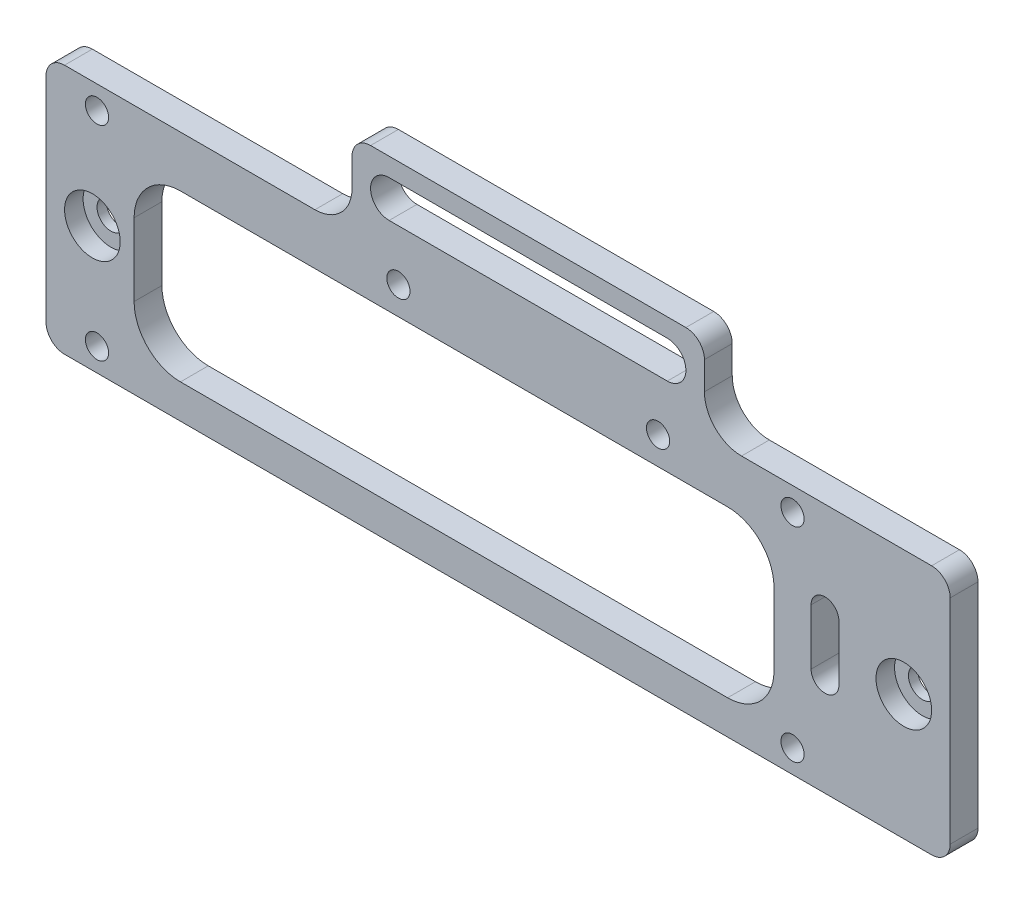
SolidWorks part; units mm, degrees
material "3.0205 (EN-AW 1200)"
ref_plane "前视基准面" through (0, 0, 0) normal (0, 0, 1) x (1, 0, 0)
ref_plane "上视基准面" through (0, 0, 0) normal (0, 1, 0) x (1, 0, 0)
ref_plane "右视基准面" through (0, 0, 0) normal (1, 0, 0) x (0, 0, -1)
other "Configuration Table"
sketch "草图3" plane through (0, 0, 0) normal (0, 0, 1) x (1, 0, 0)
  line L2 (-48.75, 13.5) -> (-48.75, -13.5)
  line L3 (-48.75, -13.5) -> (48.75, -13.5)
  line L4 (48.75, 13.5) -> (48.75, -13.5)
  line L5 (-48.75, 13.5) -> (48.75, -13.5) construction
  line L6 (-48.75, -13.5) -> (48.75, 13.5) construction
  line L16 (-48.75, 13.5) -> (48.75, 13.5)
  point P0 (0, 0)
  dimension "D1" = 97.5
  dimension "D2" = 27
extrude "凸台-拉伸1" add sketch "草图3" along normal blind 3
sketch "草图4" plane through (0, 0, 3) normal (0, 0, 1) x (1, 0, 0)
  line L0 (-48.75, 13.5) -> (-48.75, -13.5) construction
  line L2 (48.75, 13.5) -> (-48.75, 13.5) construction
  circle A0 centre (-43.25, 11) radius 1.25
  circle A1 centre (-43.25, -11) radius 1.25
  circle A2 centre (31.75, 11) radius 1.25
  circle A3 centre (31.75, -11) radius 1.25
  circle A4 centre (17.25, 11) radius 1.25
  circle A5 centre (-10.75, 11) radius 1.25
  dimension "D1" = 2.5
  dimension "D2" = 2.5
  dimension "D3" = 2.5
  dimension "D4" = 2.5
  dimension "D9" = 2.5
  dimension "D10" = 2.5
  dimension "D5" = 5.5
  dimension "D6" = 2.5
  dimension "D7" = 22
  dimension "D8" = 75
  dimension "D11" = 14.5
  dimension "D12" = 28
extrude "切除-拉伸1" cut sketch "草图4" against normal through all
sketch "草图7" plane through (0, 0, 0) normal (0, 0, -1) x (-1, 0, 0)
  line L0 (48.75, 13.5) -> (48.75, -13.5) construction
  line L1 (48.75, -3.5) -> (44.75, -3.5)
  line L2 (48.75, -3.5) -> (48.75, 4.5)
  line L3 (48.75, 4.5) -> (44.75, 4.5)
  line L4 (44.75, -3.5) -> (44.75, 4.5)
  line L5 (-48.75, -13.5) -> (-48.75, 13.5) construction
  line L6 (-48.75, -3.5) -> (-44.75, -3.5)
  line L7 (-48.75, -3.5) -> (-48.75, 4.5)
  line L8 (-48.75, 4.5) -> (-44.75, 4.5)
  line L9 (-44.75, -3.5) -> (-44.75, 4.5)
  line L10 (48.75, -13.5) -> (-48.75, -13.5) construction
  line L11 (48.75, -13.5) -> (-48.75, -13.5) construction
  dimension "D1" = 4
  dimension "D2" = 4
  dimension "D3" = 8
  dimension "D4" = 8
  dimension "D5" = 10
  dimension "D6" = 10
extrude "凸台-拉伸2" add sketch "草图7" along normal blind 5
sketch "草图8" plane through (0, 0, 3) normal (0, 0, 1) x (1, 0, 0)
  line L0 (-11.75, 18.5) -> (18.25, 18.5) construction
  line L1 (48.75, 13.5) -> (-48.75, 13.5) construction
  line L2 (-48.75, 13.5) -> (-48.75, -13.5) construction
  line L3 (-11.75, 20.5) -> (18.25, 20.5)
  line L4 (-15.75, 13.5) -> (22.25, 13.5)
  line L5 (-15.75, 13.5) -> (-15.75, 22.5)
  line L6 (-15.75, 22.5) -> (22.25, 22.5)
  line L7 (22.25, 13.5) -> (22.25, 22.5)
  line L8 (-11.75, 16.5) -> (18.25, 16.5)
  arc A0 (-11.75, 20.5) -> (-11.75, 16.5) centre (-11.75, 18.5) ccw
  arc A1 (18.25, 16.5) -> (18.25, 20.5) centre (18.25, 18.5) ccw
  point P10 (3.25, 18.5)
  dimension "D4" = 2
  dimension "D1" = 38
  dimension "D2" = 33
  dimension "D3" = 9
  dimension "D5" = 5
  dimension "D6" = 4
  dimension "D7" = 4
extrude "凸台-拉伸3" add sketch "草图8" against normal up to surface (3 mm away) up to face at (-9.5, 11, 0)
fillet "圆角3" radius 4 2 edges at (22.25, 13.5, 1.5) (-15.75, 13.5, 1.5)
fillet "圆角4" radius 2 2 edges at (-15.75, 22.5, 1.5) (22.25, 22.5, 1.5)
sketch "草图9" plane through (0, 0, -5) normal (0, 0, -1) x (-1, 0, 0)
  line L4 (-48.75, 4.5) -> (-48.75, -3.5)
  line L5 (-48.75, -3.5) -> (-44.75, -3.5)
  line L6 (-44.75, -3.5) -> (-44.75, 4.5)
  line L7 (-44.75, 4.5) -> (-48.75, 4.5)
  line L8 (-48.75, 4.5) -> (-48.75, -3.5)
  line L9 (-48.75, -3.5) -> (-44.75, -3.5)
  line L10 (-44.75, -3.5) -> (-44.75, 4.5)
  line L11 (-44.75, 4.5) -> (-48.75, 4.5)
  line L12 (48.75, -3.5) -> (48.75, 4.5)
  line L13 (48.75, 4.5) -> (44.75, 4.5)
  line L14 (44.75, 4.5) -> (44.75, -3.5)
  line L15 (44.75, -3.5) -> (48.75, -3.5)
  line L16 (48.75, -3.5) -> (48.75, 4.5)
  line L17 (48.75, 4.5) -> (44.75, 4.5)
  line L18 (44.75, 4.5) -> (44.75, -3.5)
  line L19 (44.75, -3.5) -> (48.75, -3.5)
  dimension "D1" = 0
  dimension "D2" = 0
extrude "切除-拉伸4" cut sketch "草图9" against normal up to surface (5 mm away) and the other way through all up to face at (-9.5, 11, 0)
sketch "草图13" plane through (0, 0, 0) normal (0, 0, -1) x (-1, 0, 0)
  line L0 (-48.75, -13.5) -> (-48.75, 13.5) construction
  line L1 (48.75, 13.5) -> (48.75, -13.5) construction
  circle A0 centre (-43.75, 0) radius 1.5
  circle A2 centre (43.75, 0) radius 1.5
  point P8 (-48.75, 0)
  dimension "D1" = 3
  dimension "D2" = 3
  dimension "D3" = 5
  dimension "D4" = 5
extrude "切除-拉伸7" cut sketch "草图13" against normal through all
sketch "草图14" plane through (0, 0, 3) normal (0, 0, 1) x (1, 0, 0)
  line L0 (35.25, 3.35) -> (35.25, -2.65) construction
  line L1 (36.75, 3.35) -> (36.75, -2.65)
  line L2 (33.75, 3.35) -> (33.75, -2.65)
  line L4 (48.75, 13.5) -> (26.25, 13.5) construction
  line L5 (48.75, -13.5) -> (48.75, 13.5) construction
  arc A0 (36.75, 3.35) -> (33.75, 3.35) centre (35.25, 3.35) ccw
  arc A1 (33.75, -2.65) -> (36.75, -2.65) centre (35.25, -2.65) ccw
  point P2 (35.25, 0.35)
  dimension "D3" = 1.5
  dimension "D1" = 12
  dimension "D2" = 10.15
  dimension "D4" = 6
extrude "切除-拉伸8" cut sketch "草图14" against normal through all
sketch "草图16" plane through (0, 0, 3) normal (0, 0, 1) x (1, 0, 0)
  circle A0 centre (-43.75, 0) radius 3
  circle A1 centre (43.75, 0) radius 3
  dimension "D1" = 6
extrude "切除-拉伸9" cut sketch "草图16" against normal blind 2
sketch "草图17" plane through (0, 0, 0) normal (0, 0, -1) x (-1, 0, 0)
  line L0 (-31.75, 11) -> (43.25, -11) construction
  line L1 (43.25, 11) -> (-31.75, -11) construction
  line L3 (39.25, -8) -> (-27.75, -8) construction
  line L4 (39.25, -8) -> (39.25, 8)
  line L5 (39.25, 8) -> (-27.75, 8)
  line L6 (-27.75, -8) -> (-27.75, 8) construction
  line L7 (39.25, -8) -> (-27.75, 8) construction
  line L8 (39.25, 8) -> (-27.75, -8) construction
  line L9 (-27.75, -8) -> (39.25, -8) construction
  line L10 (-27.75, -8) -> (-27.75, -9.8267) construction
  line L11 (-27.75, -9.8267) -> (39.25, -9.8267)
  line L12 (39.25, -8) -> (39.25, -9.8267)
  line L13 (-27.75, 8) -> (-29.75, 8)
  line L14 (-27.75, 8) -> (-27.75, -9.8267) construction
  line L15 (-27.75, -9.8267) -> (-29.75, -9.8267)
  line L16 (-29.75, 8) -> (-29.75, -9.8267)
  circle A0 centre (-31.75, 11) radius 1.25 construction
  circle A1 centre (-17.25, 11) radius 1.25 construction
  point P8 (5.75, 0)
  dimension "D2" = 3
  dimension "D1" = 4
  dimension "D3" = 2
extrude "切除-拉伸10" cut sketch "草图17" against normal blind 10
fillet "圆角5" radius 5 4 edges at (-39.25, 8, 1.5) (-39.25, -9.8267, 1.5) (29.75, -9.8267, 1.5) (29.75, 8, 1.5)
fillet "圆角6" radius 2 4 edges at (-48.75, 13.5, 1.5) (-48.75, -13.5, 1.5) (48.75, -13.5, 1.5) (48.75, 13.5, 1.5)
